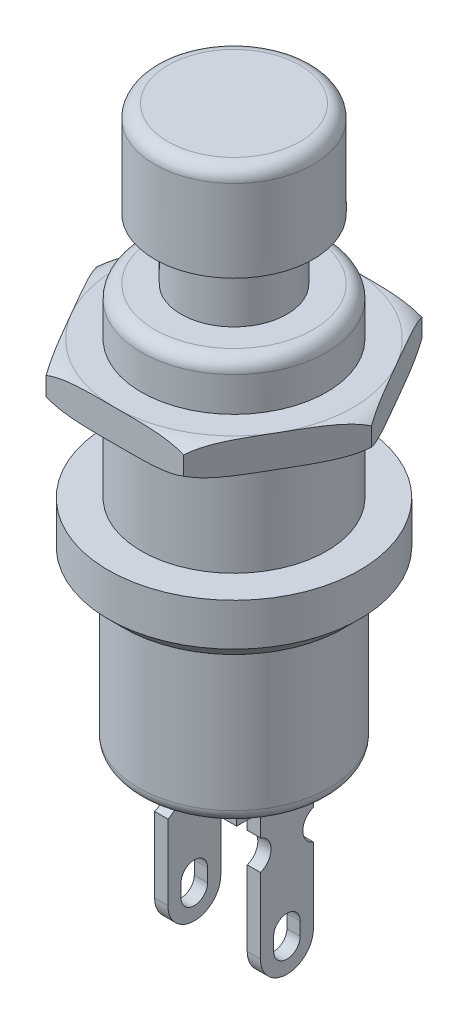
SolidWorks part; units mm, degrees
ref_plane "Front Plane" through (0, 0, 0) normal (0, 0, 1) x (1, 0, 0)
ref_plane "Top Plane" through (0, 0, 0) normal (0, 1, 0) x (1, 0, 0)
ref_plane "Right Plane" through (0, 0, 0) normal (1, 0, 0) x (0, 0, -1)
sketch "Sketch1" plane through (0, 0, 0) normal (0, 0, 1) x (1, 0, 0)
  line L0 (0, 0) -> (3.6, 0)
  line L1 (3.6, 0) -> (3.6, 6)
  line L2 (3.6, 6) -> (4.15, 6)
  line L3 (4.15, 6) -> (4.75, 6.6)
  line L4 (4.75, 6.6) -> (4.75, 8.2)
  line L5 (4.75, 8.2) -> (3.5, 8.2)
  line L6 (3.5, 8.2) -> (3.5, 15.2)
  line L7 (3.5, 15.2) -> (2, 15.2)
  line L8 (2, 15.2) -> (2, 17.5)
  line L9 (2, 17.5) -> (3, 17.5)
  line L10 (3, 17.5) -> (3, 21.1)
  line L11 (3, 21.1) -> (0, 21.1)
  line L12 (0, 21.1) -> (0, 0)
  dimension "D1" = 3
  dimension "D2" = 3.6
  dimension "D3" = 2.3
  dimension "D4" = 3.5
  dimension "D5" = 7
  dimension "D6" = 8.2
  dimension "D7" = 3.6
  dimension "D8" = 4.75
  dimension "D9" = 135
  dimension "D10" = 1.6
  dimension "D11" = 0.6
  dimension "D12" = 2
revolve "Revolve1" add sketch "Sketch1" angle 360 about L12
fillet "Fillet1" radius 0.5 3 edges at (-3.5, 15.2, 0) (-3, 21.1, 0) (-3.6, 0, 0)
sketch "Sketch2" plane through (0, 0, 0) normal (1, 0, 0) x (0, 0, -1)
  line L0 (-1.9, 0) -> (-1.9, -0.6)
  line L1 (-3.1, 0) -> (3.1, 0) construction
  line L2 (-1.9, -0.6) -> (-1, -0.6)
  line L3 (1, -5.4) -> (1, -0.6)
  line L4 (-1, -0.6) -> (-1, -5.4)
  line L5 (1, -0.6) -> (1.9, -0.6)
  line L6 (1.9, -0.6) -> (1.9, 0)
  line L7 (1.9, 0) -> (-1.9, 0)
  arc A0 (-1, -5.4) -> (1, -5.4) centre (0, -5.4) ccw
  dimension "D1" = 1
  dimension "D2" = 5.4
  dimension "D3" = 0.6
  dimension "D4" = 3.8
extrude "Boss-Extrude1" add sketch "Sketch2" along normal blind 0.5 from offset 1.5
sketch "Sketch3" plane through (2, 0, 0) normal (1, 0, 0) x (0, 0, -1)
  line L2 (0, -5.4) -> (0, -4.9) construction
  line L3 (-0.5, -5.4) -> (-0.5, -4.9)
  line L4 (0.5, -5.4) -> (0.5, -4.9)
  line L5 (-1, -0.6) -> (-1, -5.4) construction
  line L6 (1, -5.4) -> (1, -0.6) construction
  line L7 (1.9, 0) -> (-1.9, 0) construction
  circle A0 centre (-1.2, -2) radius 0.6
  circle A1 centre (1.2, -2) radius 0.6
  arc A2 (-0.5, -5.4) -> (0.5, -5.4) centre (0, -5.4) ccw
  arc A3 (0.5, -4.9) -> (-0.5, -4.9) centre (0, -4.9) ccw
  arc A5 (-1, -5.4) -> (1, -5.4) centre (0, -5.4) ccw construction
  point P11 (0, -5.15)
  dimension "D1" = 0.5
  dimension "D3" = 1.2
  dimension "D2" = 0.5
  dimension "D4" = 0.2
  dimension "D5" = 0.2
  dimension "D6" = 2
extrude "Cut-Extrude1" cut sketch "Sketch3" against normal up to next
mirror "Mirror1" about plane through (0, 0, 0) normal (1, 0, 0) of "Cut-Extrude1", "Boss-Extrude1"
sketch "Sketch4" plane through (0, 8.2, 0) normal (0, 1, 0) x (1, 0, 0)
  line L1 (5.1962, 0) -> (2.5981, 4.5)
  line L2 (2.5981, 4.5) -> (-2.5981, 4.5)
  line L3 (-2.5981, 4.5) -> (-5.1962, 0)
  line L4 (-5.1962, 0) -> (-2.5981, -4.5)
  line L5 (-2.5981, -4.5) -> (2.5981, -4.5)
  line L6 (2.5981, -4.5) -> (5.1962, 0)
  circle A0 centre (0, 0) radius 4.5 construction
  circle A1 centre (0, 0) radius 3.5
  dimension "D1" = 9
extrude "Boss-Extrude2" add sketch "Sketch4" along normal blind 1.2 from offset 4
sketch "Sketch5" plane through (0, 0, 0) normal (0, 0, 1) x (1, 0, 0)
  line L0 (-5.1962, 13.4) -> (-4.5, 13.4)
  line L1 (-5.1962, 13.4) -> (-2.5981, 13.4) construction
  line L2 (-5.1962, 13.4) -> (-5.1962, 12.2) construction
  line L3 (-5.1962, 13.15) -> (-5.1962, 13.4)
  line L4 (-4.5, 12.2) -> (-5.1962, 12.2)
  line L5 (-5.1962, 12.2) -> (-2.5981, 12.2) construction
  line L6 (-5.1962, 12.2) -> (-5.1962, 12.45)
  line L7 (0, 13.4) -> (0, 12.2) construction
  line L8 (-2.5981, 13.4) -> (2.5981, 13.4) construction
  line L9 (-2.5981, 12.2) -> (2.5981, 12.2) construction
  arc A0 (-4.5, 13.4) -> (-5.1962, 13.15) centre (-4.5, 12.3057) ccw
  arc A1 (-5.1962, 12.45) -> (-4.5, 12.2) centre (-4.5, 13.2943) ccw
  dimension "D1" = 0.25
  dimension "D2" = 4.5
revolve "Cut-Revolve1" cut sketch "Sketch5" angle 360 about L7
